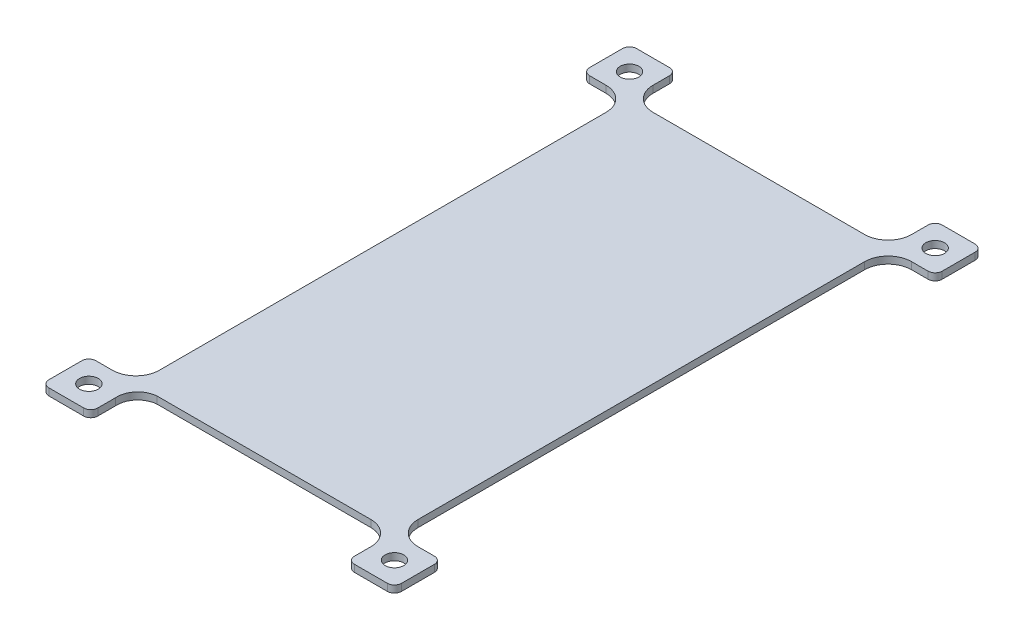
SolidWorks part; units mm, degrees
ref_plane "Front Plane" through (0, 0, 0) normal (0, 0, 1) x (1, 0, 0)
ref_plane "Top Plane" through (0, 0, 0) normal (0, 1, 0) x (1, 0, 0)
ref_plane "Right Plane" through (0, 0, 0) normal (1, 0, 0) x (0, 0, -1)
sketch "Sketch1" plane through (0, 0, 0) normal (0, 1, 0) x (1, 0, 0)
  line L0 (-45, 105) -> (45, 105)
  line L1 (-75, 125) -> (-55, 125)
  line L2 (-75, 125) -> (-75, 105)
  line L3 (-75, -125) -> (-54.2021, -125)
  line L4 (75, 125) -> (75, 105)
  line L5 (-75, 125) -> (75, -125) construction
  line L6 (-75, -125) -> (75, 125) construction
  line L7 (55, 95) -> (55, -95)
  line L8 (-46, -105) -> (45, -105)
  line L9 (-55, 95) -> (-55, -95)
  line L10 (-55, 115) -> (-55, 125)
  line L11 (55, 115) -> (55, 125)
  line L12 (-54.2021, -113.2021) -> (-54.2021, -125)
  line L13 (55, -115) -> (55, -125)
  line L14 (-65, -105) -> (-75, -105)
  line L15 (65, -105) -> (75, -105)
  line L16 (-65, 105) -> (-75, 105)
  line L17 (-55, -105) -> (55, -105) construction
  line L18 (-55, 105) -> (-55, -105) construction
  line L19 (55, 105) -> (55, -105) construction
  line L20 (65, 105) -> (75, 105)
  line L21 (-55, 105) -> (55, 105) construction
  line L22 (75, -105) -> (75, -125)
  line L23 (75, 125) -> (75, -125) construction
  line L24 (-75, -105) -> (-75, -125)
  line L25 (-75, 125) -> (-75, -125) construction
  line L26 (55, 125) -> (75, 125)
  line L27 (-75, 125) -> (75, 125) construction
  line L28 (55, -125) -> (75, -125)
  line L29 (-75, -125) -> (75, -125) construction
  line L30 (55, 125) -> (75, 105) construction
  line L31 (0, 105) -> (0, 147.4431) construction
  line L32 (0, 0) -> (92.1337, 0) construction
  arc A0 (-54.2021, -114.5381) -> (-46, -105) centre (-45.332, -113.8701) cw
  arc A1 (-55, -95) -> (-65, -105) centre (-65, -95) cw
  arc A2 (45, -105) -> (55, -115) centre (44.9247, -115.0753) cw
  arc A3 (65, -105) -> (55, -95) centre (65, -95) cw
  arc A4 (-65, 105) -> (-55, 95) centre (-65, 95) cw
  arc A5 (-45, 105) -> (-55, 115) centre (-45, 115) cw
  arc A6 (55, 95) -> (65, 105) centre (65, 95) cw
  arc A7 (55, 115) -> (45, 105) centre (45, 115) cw
  circle A8 centre (65, 115) radius 3.9688
  circle A9 centre (-65, 115) radius 3.9687
  circle A10 centre (65, -115) radius 3.9688
  circle A11 centre (-65, -115) radius 3.9687
  point P0 (0, 0)
  dimension "D1" = 20
  dimension "D2" = 10
  dimension "D3" = 10
  dimension "D4" = 10
  dimension "D5" = 10
  dimension "D6" = 10
  dimension "D7" = 10
  dimension "D8" = 10
extrude "Boss-Extrude1" add sketch "Sketch1" along normal blind 3 contours L11 A7 L0 A5 L10 L1 L2 L16 A4 L9 A1 L14 L24 L3 L12 A0 L8 A2 L13 L28 L22 L15 A3 L7 A6 L20 L4 L26
fillet "Fillet1" radius 3 12 edges at (75, 1.5, 105) (55, 1.5, 125) (75, 1.5, 125) (75, 1.5, -105) (75, 1.5, -125) (55, 1.5, -125) (-55, 1.5, -125) (-75, 1.5, -125) (-75, 1.5, -105) (-75, 1.5, 105) (-75, 1.5, 125) (-54.2021, 1.5, 125)
sketch "Sketch9" plane through (0, 0, 0) normal (1, 0, 0) x (0, 0, -1)
  line L0 (95, 0) -> (-95, 0) construction
  line L1 (-15, 0) -> (15, 0)
  line L2 (-15, 0) -> (-15, -15.6)
  line L3 (-0.6, -30) -> (0.6, -30)
  line L4 (15, 0) -> (15, -15.6)
  circle A0 centre (0, -15) radius 4.7625
  arc A1 (0.6, -30) -> (15, -15.6) centre (0.6, -15.6) ccw
  arc A2 (-15, -15.6) -> (-0.6, -30) centre (-0.6, -15.6) ccw
  point P13 (-15, -30)
  dimension "D4" = 15
  dimension "D5" = 14.4
  dimension "D1" = 15
  dimension "D2" = 30
  dimension "D3" = 30
extrude "Boss-Extrude3" add sketch "Sketch9" along normal mid plane 10
